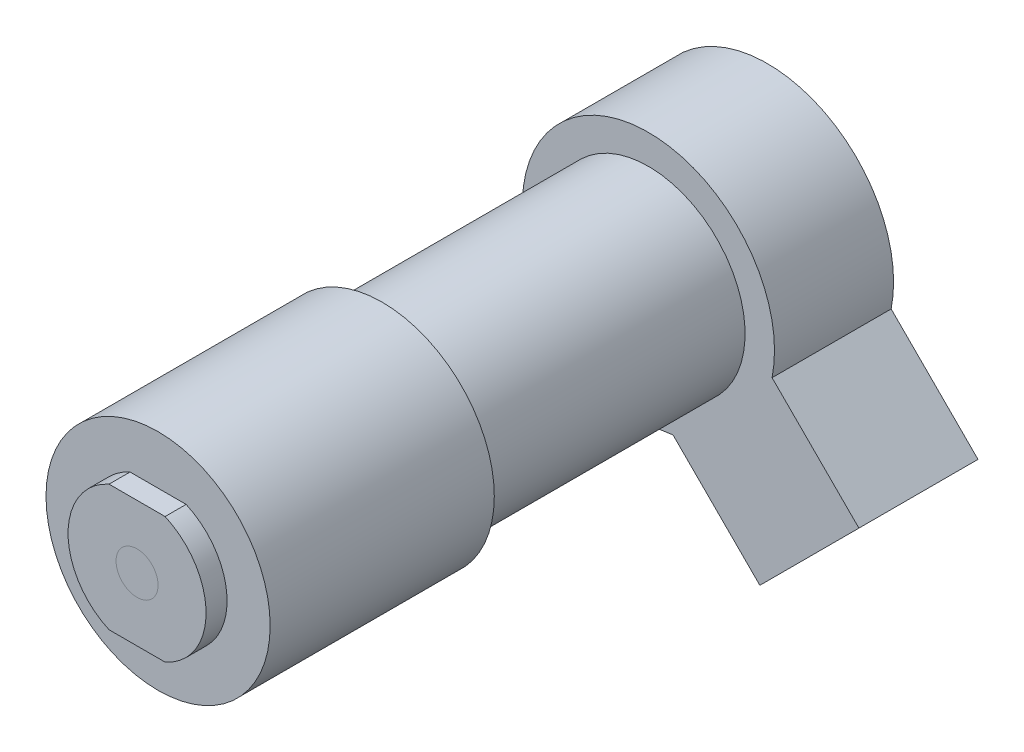
SolidWorks part; units mm, degrees
ref_plane "Front Plane" through (0, 0, 0) normal (0, 0, 1) x (1, 0, 0)
ref_plane "Top Plane" through (0, 0, 0) normal (0, 1, 0) x (1, 0, 0)
ref_plane "Right Plane" through (0, 0, 0) normal (1, 0, 0) x (0, 0, -1)
sketch "Sketch1" plane through (0, 0, 0) normal (0, 0, 1) x (1, 0, 0)
  line L0 (0, 0) -> (0, 9) construction
  line L1 (-4.0028, 9) -> (4.0028, 9)
  line L2 (-9.85, 0) -> (9.85, 0) construction
  line L3 (-4.0028, -9) -> (4.0028, -9)
  arc A0 (-4.0028, 9) -> (-4.0028, -9) centre (0, 0) ccw
  arc A1 (4.0028, -9) -> (4.0028, 9) centre (0, 0) ccw
  point P7 (0, 9)
  point P10 (0, 0)
  dimension "D1" = 19.7
  dimension "D2" = 9
extrude "Boss-Extrude1" add sketch "Sketch1" along normal blind 3
sketch "Sketch2" plane through (0, 0, 0) normal (0, 0, -1) x (-1, 0, 0)
  circle A0 centre (0, 0) radius 16
  dimension "D1" = 32
extrude "Boss-Extrude2" add sketch "Sketch2" along normal blind 32
sketch "Sketch3" plane through (0, 0, -32) normal (0, 0, -1) x (-1, 0, 0)
  circle A0 centre (0, 0) radius 13.8
  dimension "D1" = 27.6
extrude "Boss-Extrude3" add sketch "Sketch3" along normal blind 38
sketch "Sketch4" plane through (0, 0, -70) normal (0, 0, -1) x (-1, 0, 0)
  line L0 (0, 0) -> (0, -18) construction
  line L1 (0, 0) -> (-22.981, -22.981) construction
  line L2 (-30.052, -15.9099) -> (-15.9099, -30.052)
  line L3 (-30.052, -15.9099) -> (-17.6541, -3.5119)
  line L4 (-15.9099, -30.052) -> (-3.5119, -17.6541)
  circle A0 centre (0, 0) radius 18
  point P7 (-22.981, -22.981)
  circle M5 centre (0, 0) radius 13.8
  dimension "D1" = 36
  dimension "D2" = 45
  dimension "D3" = 32.5
  dimension "D4" = 20
extrude "Boss-Extrude4" add sketch "Sketch4" along normal blind 17 contours A0 M5 | M5 | A0 L3 L2 L4
sketch "Sketch5" plane through (0, 0, 3) normal (0, 0, 1) x (1, 0, 0)
  circle A0 centre (0, 0) radius 3
  dimension "D1" = 6
split line "Split Line1"
